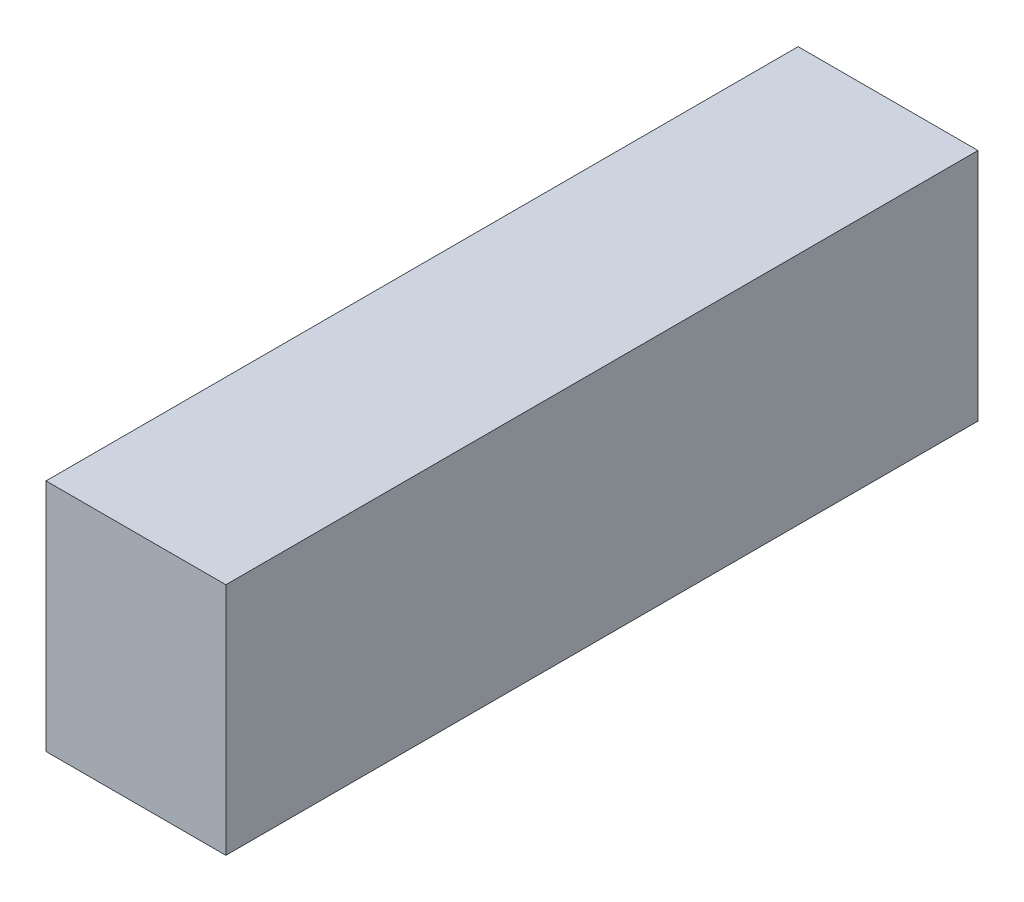
SolidWorks part; units mm, degrees
material "ABS"
ref_plane "Front" through (0, 0, 0) normal (0, 0, 1) x (1, 0, 0)
ref_plane "Top" through (0, 0, 0) normal (0, 1, 0) x (1, 0, 0)
ref_plane "Right" through (0, 0, 0) normal (1, 0, 0) x (0, 0, -1)
sketch "Sketch1" plane through (0, 0, 0) normal (1, 0, 0) x (0, 0, -1)
  line L1 (0, 0) -> (138, 0)
  line L2 (0, 0) -> (0, -43)
  line L3 (0, -43) -> (138, -43)
  line L4 (138, 0) -> (138, -43)
  dimension "D1" = 138
  dimension "D2" = 43
extrude "Boss-Extrude1" add sketch "Sketch1" along normal blind 33
